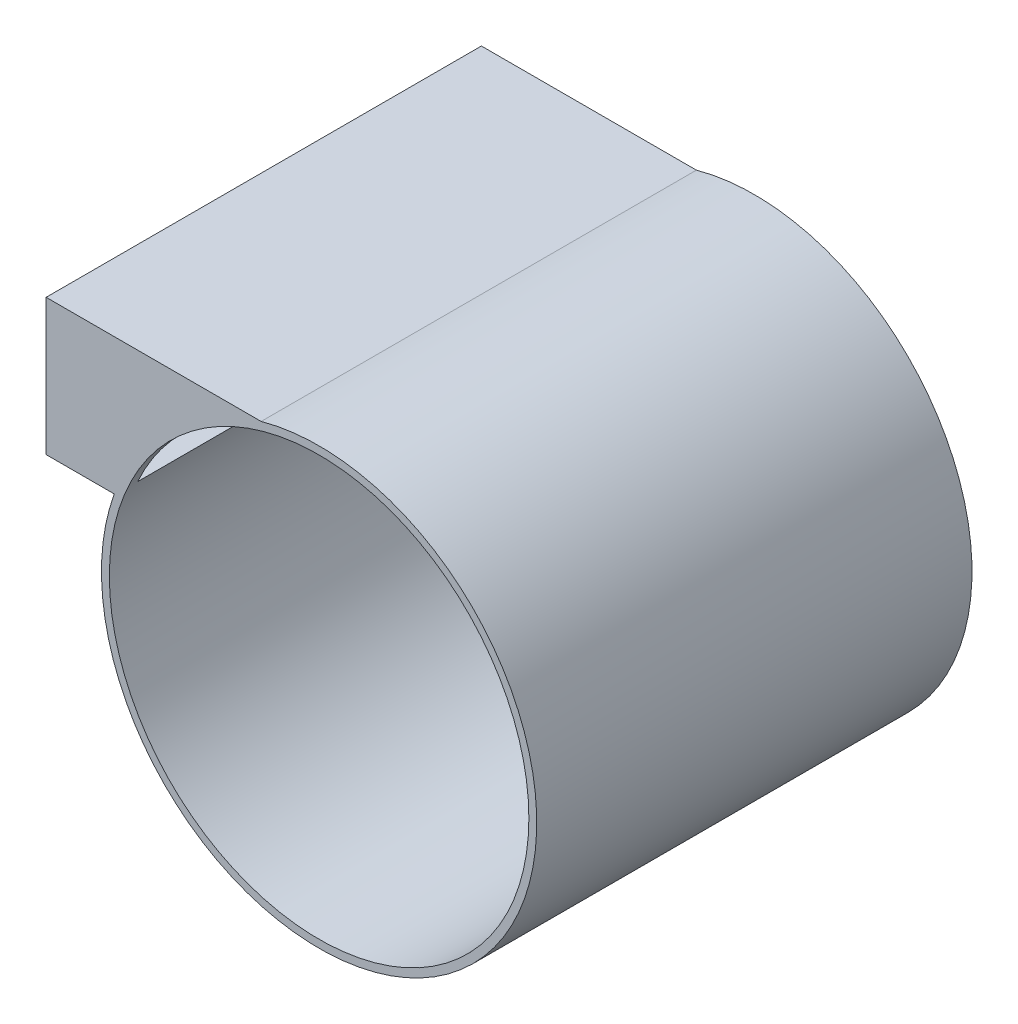
SolidWorks part; units mm, degrees
ref_plane "Front Plane" through (0, 0, 0) normal (0, 0, 1) x (1, 0, 0)
ref_plane "Top Plane" through (0, 0, 0) normal (0, 1, 0) x (1, 0, 0)
ref_plane "Right Plane" through (0, 0, 0) normal (1, 0, 0) x (0, 0, -1)
sketch "Sketch1" plane through (0, 0, 0) normal (0, 0, 1) x (1, 0, 0)
  circle A0 centre (0, 0) radius 105.41
extrude "Boss-Extrude1" add sketch "Sketch1" along normal blind 210.82
sketch "Sketch2" plane through (0, 0, 210.82) normal (0, 0, 1) x (1, 0, 0)
  circle A0 centre (0, 0) radius 101.6
extrude "Cut-Extrude1" cut sketch "Sketch2" against normal blind 203.2
sketch "Sketch3" plane through (0, 0, 7.62) normal (0, 0, 1) x (1, 0, 0)
  line L1 (0, 35.6047) -> (-132.2166, 35.6047)
  line L2 (0, 35.6047) -> (0, 101.6)
  line L3 (0, 101.6) -> (-132.2166, 101.6)
  line L4 (-132.2166, 35.6047) -> (-132.2166, 101.6)
extrude "Boss-Extrude2" add sketch "Sketch3" along normal blind 203.2 and the other way blind 7.62
sketch "Sketch4" plane through (-132.2166, 0, 0) normal (-1, 0, 0) x (0, 0, 1)
  line L1 (5.258, 41.6871) -> (206.0576, 41.6871)
  line L2 (5.258, 41.6871) -> (5.258, 96.0017)
  line L3 (5.258, 96.0017) -> (206.0576, 96.0017)
  line L4 (206.0576, 41.6871) -> (206.0576, 96.0017)
extrude "Cut-Extrude2" cut sketch "Sketch4" against normal blind 147.574
sketch "Sketch5" plane through (0, 0, 210.82) normal (0, 0, 1) x (1, 0, 0)
  circle A0 centre (0, 0) radius 101.6
extrude "Cut-Extrude3" cut sketch "Sketch5" against normal blind 147.574
sketch "Sketch6" plane through (0, 0, 63.246) normal (0, 0, 1) x (1, 0, 0)
  circle A0 centre (0, 0) radius 101.6
extrude "Cut-Extrude4" cut sketch "Sketch6" against normal blind 60.706
